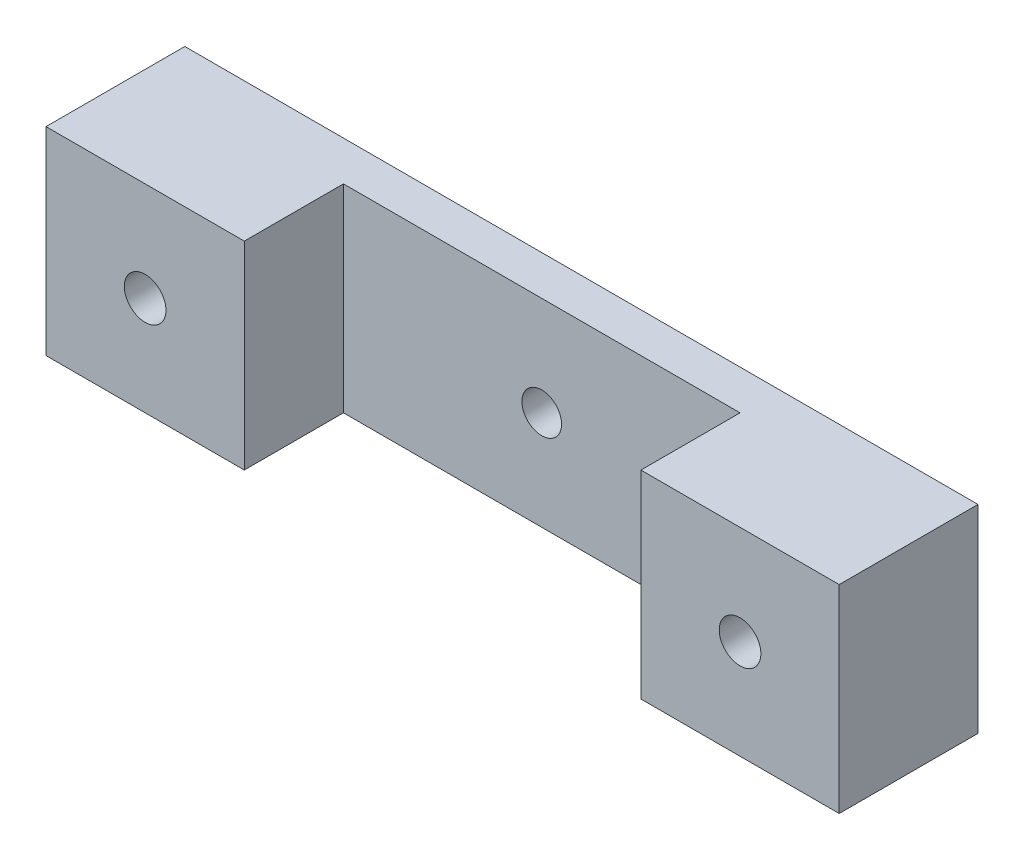
SolidWorks part; units mm, degrees
ref_plane "前视基准面" through (0, 0, 0) normal (0, 0, 1) x (1, 0, 0)
ref_plane "上视基准面" through (0, 0, 0) normal (0, 1, 0) x (1, 0, 0)
ref_plane "右视基准面" through (0, 0, 0) normal (1, 0, 0) x (0, 0, -1)
sketch "草图1" plane through (0, 0, 0) normal (0, 0, 1) x (1, 0, 0)
  line L1 (0, 0) -> (80, 0)
  line L2 (0, 0) -> (0, 20)
  line L3 (0, 20) -> (80, 20)
  line L4 (80, 0) -> (80, 20)
  dimension "D1" = 20
  dimension "D2" = 80
extrude "凸台-拉伸1" add sketch "草图1" along normal blind 4
sketch "草图2" plane through (0, 0, 4) normal (0, 0, 1) x (1, 0, 0)
  line L0 (0, 0) -> (80, 0) construction
  line L1 (0, 20) -> (20, 20)
  line L2 (0, 20) -> (0, 0)
  line L3 (0, 0) -> (20, 0)
  line L4 (20, 20) -> (20, 0)
  line L6 (80, 20) -> (60, 20)
  line L7 (80, 20) -> (80, 0)
  line L8 (80, 0) -> (60, 0)
  line L9 (60, 20) -> (60, 0)
  dimension "D1" = 20
  dimension "D2" = 20
extrude "凸台-拉伸2" add sketch "草图2" along normal blind 10
sketch "草图3" plane through (0, 0, 14) normal (0, 0, 1) x (1, 0, 0)
  line L0 (0, 0) -> (20, 0) construction
  line L1 (0, 20) -> (0, 0) construction
  line L2 (60, 0) -> (80, 0) construction
  line L3 (60, 20) -> (60, 0) construction
  circle A0 centre (10, 10) radius 2.1
  circle A1 centre (70, 10) radius 2.1
  dimension "D1" = 4.2
  dimension "D2" = 4.2
  dimension "D3" = 10
  dimension "D4" = 10
  dimension "D5" = 10
  dimension "D6" = 10
extrude "切除-拉伸1" cut sketch "草图3" against normal blind 20
sketch "草图4" plane through (0, 0, 0) normal (0, 0, -1) x (-1, 0, 0)
  line L0 (0, 0) -> (-80, 0) construction
  line L1 (0, 20) -> (0, 0) construction
  circle A0 centre (-40, 10) radius 2
  dimension "D1" = 4
  dimension "D2" = 10
  dimension "D3" = 40
extrude "切除-拉伸2" cut sketch "草图4" against normal blind 20
